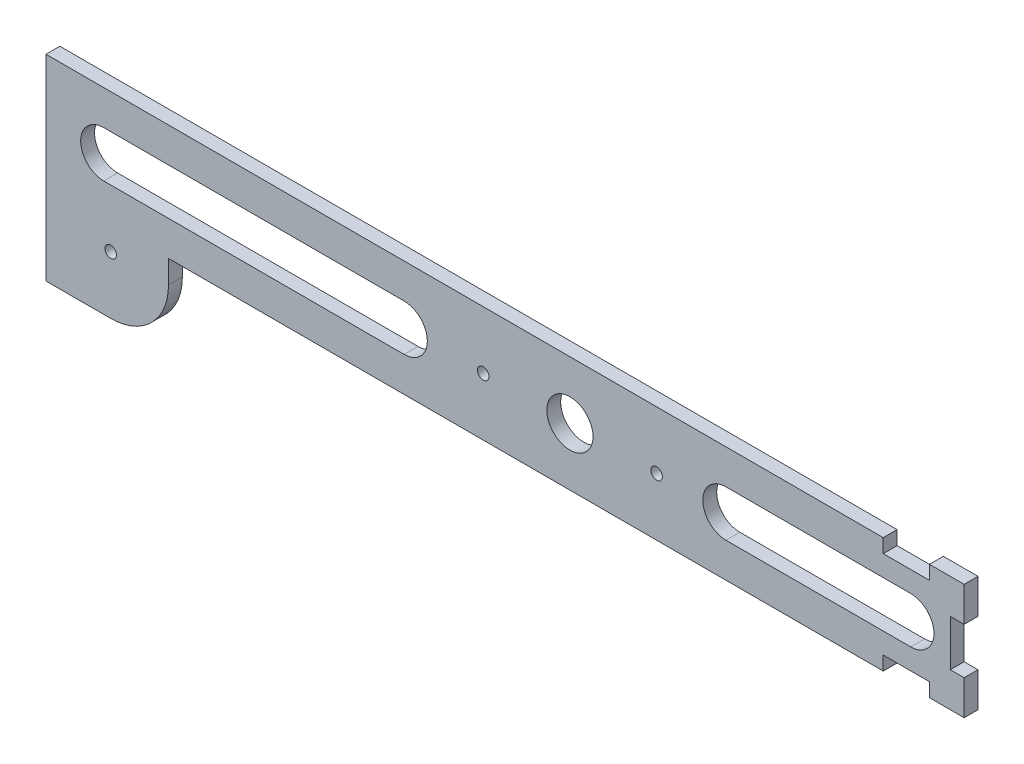
SolidWorks part; units mm, degrees
material "Teak"
ref_plane "Front Plane" through (0, 0, 0) normal (0, 0, 1) x (1, 0, 0)
ref_plane "Top Plane" through (0, 0, 0) normal (0, 1, 0) x (1, 0, 0)
ref_plane "Right Plane" through (0, 0, 0) normal (1, 0, 0) x (0, 0, -1)
sketch "Sketch1" plane through (0, 0, 0) normal (0, 0, 1) x (1, 0, 0)
  point P0 (0, 0)
  line B0 (25, -35) -> (155, -35)
  line B1 (155, -15) -> (25, -15)
  line B2 (294.2, -35) -> (374.2, -35)
  line B3 (374.2, -15) -> (294.2, -15)
  line B4 (397.27, -50) -> (397.27, -35)
  line B5 (397.27, -35) -> (391.27, -35)
  line B6 (391.27, -35) -> (391.27, -15)
  line B7 (391.27, -15) -> (397.27, -15)
  line B8 (397.27, -15) -> (397.27, 0)
  line B9 (397.27, 0) -> (382.27, 0)
  line B10 (382.27, 0) -> (382.27, -6)
  line B11 (382.27, -6) -> (362.27, -6)
  line B12 (362.27, -6) -> (362.27, 0)
  line B13 (362.27, 0) -> (0, 0)
  line B14 (0, 0) -> (0, -85)
  line B15 (0, -85) -> (28, -85)
  line B16 (53, -60) -> (53, -50)
  line B17 (53, -50) -> (362.27, -50)
  line B18 (362.27, -50) -> (362.27, -44)
  line B19 (362.27, -44) -> (382.27, -44)
  line B20 (382.27, -44) -> (382.27, -50)
  line B21 (382.27, -50) -> (397.27, -50)
  arc B22 (25, -15) -> (25, -35) centre (25, -25) ccw
  arc B23 (155, -35) -> (155, -15) centre (155, -25) ccw
  circle B24 centre (189.2, -25) radius 2.5
  arc B25 (294.2, -15) -> (294.2, -35) centre (294.2, -25) ccw
  arc B26 (374.2, -35) -> (374.2, -15) centre (374.2, -25) ccw
  circle B27 centre (226.7, -25) radius 10
  circle B28 centre (28, -60) radius 2.5
  circle B29 centre (264.2, -25) radius 2.5
  arc B30 (28, -85) -> (53, -60) centre (28, -60) ccw
sketch_block_instance "Block1-1"
sketch_block "Block1"
extrude "Boss-Extrude1" add sketch "Sketch1" along normal blind 6
